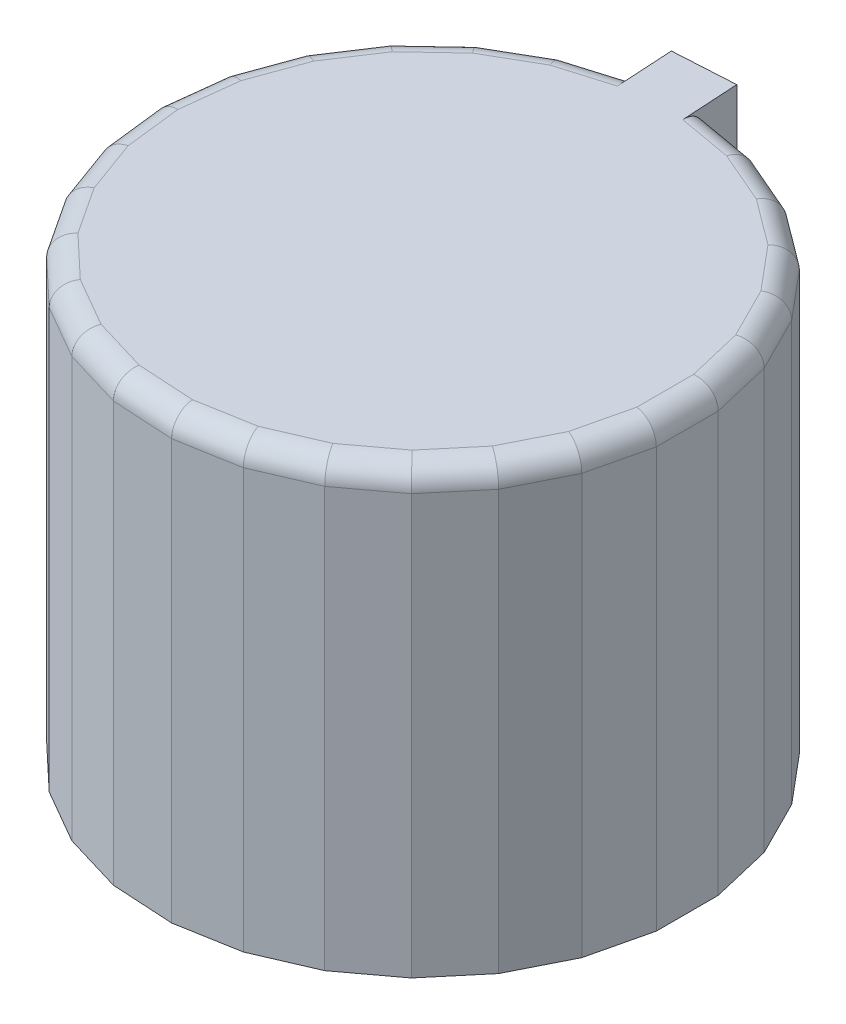
SolidWorks part; units mm, degrees
ref_plane "Front Plane" through (0, 0, 0) normal (0, 0, 1) x (1, 0, 0)
ref_plane "Top Plane" through (0, 0, 0) normal (0, 1, 0) x (1, 0, 0)
ref_plane "Right Plane" through (0, 0, 0) normal (1, 0, 0) x (0, 0, -1)
sketch "Sketch1" plane through (0, 0, 0) normal (0, 1, 0) x (1, 0, 0)
  line L0 (4.1455, 4.394) -> (3.0204, 5.2315)
  line L1 (6, 0.7013) -> (5.6765, 2.0661)
  line L2 (5.6765, 2.0661) -> (5.0471, 3.3195)
  line L3 (5.0471, 3.3195) -> (4.1455, 4.394)
  line L4 (3.0204, 5.2315) -> (1.7325, 5.7871)
  line L5 (1.7325, 5.7871) -> (0.3512, 6.0306)
  line L6 (0.3512, 6.0306) -> (-1.049, 5.9491)
  line L7 (-1.049, 5.9491) -> (-2.3927, 5.5468)
  line L8 (-2.3927, 5.5468) -> (-3.6073, 4.8455)
  line L9 (-3.6073, 4.8455) -> (-4.6276, 3.883)
  line L10 (-4.6276, 3.883) -> (-5.3983, 2.7111)
  line L11 (-5.3983, 2.7111) -> (-5.878, 1.3931)
  line L12 (-5.878, 1.3931) -> (-6.0408, 0)
  line L13 (-6.0408, 0) -> (-5.878, -1.3931)
  line L14 (-5.878, -1.3931) -> (-5.3983, -2.7111)
  line L15 (-5.3983, -2.7111) -> (-4.6276, -3.883)
  line L16 (-4.6276, -3.883) -> (-3.6073, -4.8455)
  line L17 (-3.6073, -4.8455) -> (-2.3927, -5.5468)
  line L18 (-2.3927, -5.5468) -> (-1.049, -5.9491)
  line L19 (-1.049, -5.9491) -> (0.3512, -6.0306)
  line L20 (0.3512, -6.0306) -> (1.7325, -5.7871)
  line L21 (1.7325, -5.7871) -> (3.0204, -5.2315)
  line L22 (3.0204, -5.2315) -> (4.1455, -4.394)
  line L23 (4.1455, -4.394) -> (5.0471, -3.3195)
  line L24 (5.0471, -3.3195) -> (5.6765, -2.0661)
  line L25 (5.6765, -2.0661) -> (6, -0.7013)
  line L26 (6, -0.7013) -> (6, 0.7013)
  line L28 (-2.3927, 5.5468) -> (-2.9663, 7.4628)
  line L29 (-1.049, 5.9491) -> (-1.6226, 7.8651)
  line L30 (-2.9663, 7.4628) -> (-1.6226, 7.8651)
  circle A0 centre (0, 0) radius 6 construction
  dimension "D1" = 0
  dimension "D2" = 6
  dimension "D3" = 2
extrude "Boss-Extrude1" add sketch "Sketch1" along normal blind 10
sketch "Sketch2" plane through (0, 0, 0) normal (0, 1, 0) x (1, 0, 0)
  line L4 (-1.049, 5.9491) -> (0.3512, 6.0306)
  line L5 (-1.049, 5.9491) -> (-1.0948, 6.7351)
  line L6 (0.3512, 6.0306) -> (0.3055, 6.8167)
  line L7 (-1.0948, 6.7351) -> (0.3055, 6.8167)
extrude "Boss-Extrude2" add sketch "Sketch2" along normal blind 10 contours L7 L5 L4 L6
fillet "Fillet2" radius 0.5 26 edges at (3.583, 10, 4.8127) (2.3765, 10, 5.5093) (1.0419, 10, 5.9088) (-0.3489, 10, 5.9898) (-1.7208, 10, 5.7479) (-3, 10, 5.1962) (-4.1174, 10, 4.3642) (-5.0129, 10, 3.2971) (-5.6382, 10, 2.0521) (-5.9594, 10, 0.6966) (-5.9594, 10, -0.6966) (-5.6382, 10, -2.0521) (-5.0129, 10, -3.2971) (-4.1174, 10, -4.3642) (-3, 10, -5.1962) (-1.7208, 10, -5.7479) (1.0419, 10, -5.9088) (2.3765, 10, -5.5093) (3.583, 10, -4.8127) (4.5963, 10, -3.8567) (5.3618, 10, -2.6928) (5.8383, 10, -1.3837) (6, 10, 0) (5.8383, 10, 1.3837) (5.3618, 10, 2.6928) (4.5963, 10, 3.8567)
sketch "Sketch4" plane through (0, 0, 0) normal (0, 1, 0) x (1, 0, 0)
  line L0 (0, 3.45) -> (0, -1.55)
  line L1 (-3.0822, -1.55) -> (3.0822, -1.55)
  circle A0 centre (0, 0) radius 3.45
  point P8 (0, -1.55)
  dimension "D1" = 5
  dimension "D2" = 6.9
extrude "Cut-Extrude1" cut sketch "Sketch4" along normal blind 7 contours L0 A0 L1 | L1 A0 L0
